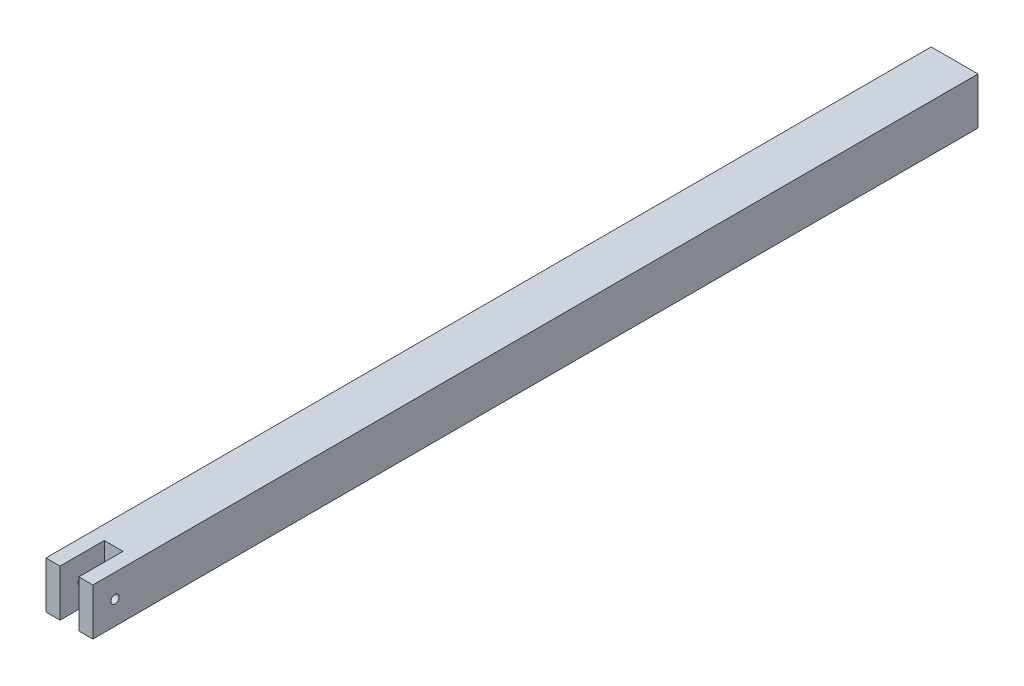
SolidWorks part; units mm, degrees
ref_plane "Front" through (0, 0, 0) normal (0, 0, 1) x (1, 0, 0)
ref_plane "Top" through (0, 0, 0) normal (0, 1, 0) x (1, 0, 0)
ref_plane "Right" through (0, 0, 0) normal (1, 0, 0) x (0, 0, -1)
sketch "Esquisse1" plane through (0, 0, 0) normal (0, 0, 1) x (1, 0, 0)
  line L1 (0, 0) -> (90, 0)
  line L2 (0, 0) -> (0, 90)
  line L3 (0, 90) -> (90, 90)
  line L4 (90, 0) -> (90, 90)
  dimension "D1" = 90
  dimension "D2" = 90
extrude "Boss.-Extru.1" add sketch "Esquisse1" along normal blind 1700
sketch "Esquisse2" plane through (0, 0, 0) normal (0, -1, 0) x (1, 0, 0)
  line L0 (0, 1700) -> (90, 1700) construction
  line L1 (27, 1700) -> (63, 1700)
  line L2 (27, 1700) -> (27, 1615)
  line L3 (27, 1615) -> (63, 1615)
  line L4 (63, 1700) -> (63, 1615)
  line L5 (45, 1615) -> (45, 1700) construction
  dimension "D1" = 36
  dimension "D2" = 85
extrude "Enlèv. mat.-Extru.1" cut sketch "Esquisse2" against normal through all
sketch "Esquisse3" plane through (90, 0, 0) normal (1, 0, 0) x (0, 0, -1)
  line L0 (-1700, 45) -> (-1657.5, 45) construction
  line L1 (-1700, 0) -> (-1700, 90) construction
  line L2 (-1657.5, 45) -> (-1615, 45) construction
  line L3 (-1615, 90) -> (-1615, 0) construction
  circle A0 centre (-1657.5, 45) radius 8
  dimension "D1" = 16
extrude "Enlèv. mat.-Extru.2" cut sketch "Esquisse3" against normal through all
